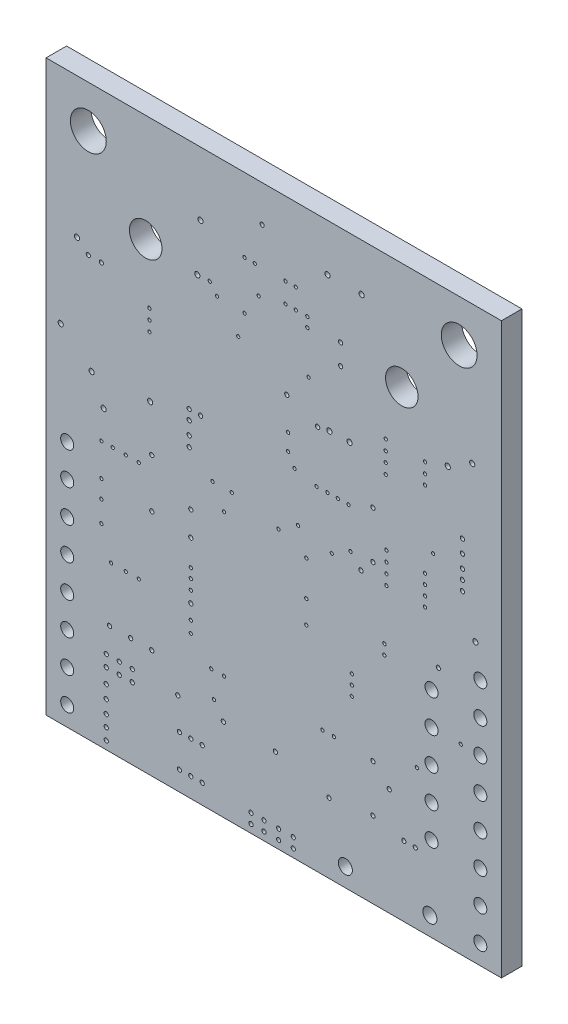
SolidWorks part; units mm, degrees
ref_plane "Front Plane" through (0, 0, 0) normal (0, 0, 1) x (1, 0, 0)
ref_plane "Top Plane" through (0, 0, 0) normal (0, 1, 0) x (1, 0, 0)
ref_plane "Right Plane" through (0, 0, 0) normal (1, 0, 0) x (0, 0, -1)
ref_plane "Dielectric_Layer Layer 1" through (0, 0, 1.6) normal (0, 0, 1) x (1, 0, 0)
sketch "Sketch1" plane through (0, 0, 0) normal (0, 0, 1) x (1, 0, 0)
  line L0 (0, 44.45) -> (0, 0)
  line L1 (0, 0) -> (35.56, 0)
  line L2 (35.56, 0) -> (35.56, 44.45)
  line L3 (35.56, 44.45) -> (0, 44.45)
extrude "Board_Outline" add sketch "Sketch1" along normal blind 1.6 separate body
sketch "Sketch2" plane through (0, 0, 0) normal (0, 0, 1) x (1, 0, 0)
  circle A0 centre (29.591, 23.622) radius 0.127
  circle A1 centre (32.385, 14.224) radius 0.127
  circle A2 centre (20.32, 18.034) radius 0.127
  circle A3 centre (13.111, 7.6) radius 0.127
  circle A4 centre (18.7, 37.15) radius 0.127
  circle A5 centre (19.676, 22.67) radius 0.127
  circle A6 centre (16.3, 38.7) radius 0.127
  circle A7 centre (18.149, 21.651) radius 0.127
  circle A8 centre (18.7, 38.7) radius 0.127
  circle A9 centre (20.322, 20.778) radius 0.127
  circle A10 centre (12.78, 35.731) radius 0.127
  circle A11 centre (19.5, 37.15) radius 0.127
  circle A12 centre (13, 22.3) radius 0.127
  circle A13 centre (13.35, 35) radius 0.127
  circle A14 centre (20.4, 37.15) radius 0.127
  circle A15 centre (18.9, 28.573) radius 0.127
  circle A16 centre (15.5, 38.7) radius 0.127
  circle A17 centre (14.5, 22.3) radius 0.127
  circle A18 centre (19.5, 38.7) radius 0.127
  circle A19 centre (13.9, 20.7) radius 0.127
  circle A20 centre (15.5, 34.925) radius 0.127
  circle A21 centre (12.899, 9.58) radius 0.127
  circle A22 centre (16.6, 36.65) radius 0.127
  circle A23 centre (13.899, 9.58) radius 0.127
  circle A24 centre (20.4, 36.4) radius 0.127
  circle A25 centre (18.9, 27.273) radius 0.127
  circle A26 centre (22.311, 22.097) radius 0.127
  circle A27 centre (20.5, 33.1) radius 0.127
  circle A28 centre (19.399, 26.384) radius 0.127
  circle A29 centre (4.318, 20.701) radius 0.127
  circle A30 centre (4.318, 16.764) radius 0.127
  circle A31 centre (5.08, 12.827) radius 0.127
  circle A32 centre (31.369, 32.512) radius 0.2032
  circle A33 centre (8.255, 21.717) radius 0.1651
  circle A34 centre (5.207, 20.701) radius 0.127
  circle A35 centre (7.239, 12.827) radius 0.127
  circle A36 centre (30.634, 18.515) radius 0.1651
  circle A37 centre (24.592, 22.079) radius 0.1651
  circle A38 centre (33.528, 21.717) radius 0.2032
  circle A39 centre (4.318, 18.161) radius 0.127
  circle A40 centre (4.318, 15.113) radius 0.127
  circle A41 centre (17.018, 0.635) radius 0.1651
  circle A42 centre (16.002, 0.635) radius 0.1651
  circle A43 centre (32.512, 24.638) radius 0.1651
  circle A44 centre (32.512, 25.4) radius 0.1651
  circle A45 centre (28.829, 5.461) radius 0.1651
  circle A46 centre (27.94, 5.461) radius 0.1651
  circle A47 centre (16.002, 1.397) radius 0.1651
  circle A48 centre (17.018, 1.397) radius 0.1651
  circle A49 centre (4.699, 0.635) radius 0.1651
  circle A50 centre (4.699, 1.524) radius 0.1651
  circle A51 centre (4.699, 2.413) radius 0.1651
  circle A52 centre (6.223, 12.827) radius 0.127
  circle A53 centre (7.239, 20.701) radius 0.127
  circle A54 centre (11.303, 17.653) radius 0.1651
  circle A55 centre (6.223, 20.701) radius 0.127
  circle A56 centre (11.176, 26.289) radius 0.1651
  circle A57 centre (12.065, 26.289) radius 0.1651
  circle A58 centre (6.604, 8.509) radius 0.1651
  circle A59 centre (8.255, 8.509) radius 0.1651
  circle A60 centre (10.287, 6.477) radius 0.1651
  circle A61 centre (17.907, 6.477) radius 0.1651
  circle A62 centre (1.143, 27.051) radius 0.2032
  circle A63 centre (4.4958, 22.987) radius 0.2032
  circle A64 centre (25.527, 26.797) radius 0.1651
  circle A65 centre (25.527, 5.969) radius 0.1651
  circle A66 centre (32.512, 26.162) radius 0.1651
  circle A67 centre (12.192, 4.064) radius 0.1651
  circle A68 centre (12.192, 1.524) radius 0.1651
  circle A69 centre (10.414, 1.524) radius 0.1651
  circle A70 centre (10.414, 4.064) radius 0.1651
  circle A71 centre (11.303, 4.064) radius 0.1651
  circle A72 centre (11.303, 1.524) radius 0.1651
  circle A73 centre (16.873, 41.6) radius 0.1651
  circle A74 centre (23, 35.1) radius 0.1651
  circle A75 centre (22.127, 30.273) radius 0.2032
  circle A76 centre (18.8, 31.0635) radius 0.1651
  circle A77 centre (11.303, 13.208) radius 0.1651
  circle A78 centre (26.5746, 23.641) radius 0.127
  circle A79 centre (21.209, 30.099) radius 0.1651
  circle A80 centre (11.176, 25.527) radius 0.1651
  circle A81 centre (24.638, 40.767) radius 0.2032
  circle A82 centre (11.811, 35.687) radius 0.2032
  circle A83 centre (21.59, 9.779) radius 0.127
  circle A84 centre (22.479, 9.779) radius 0.127
  circle A85 centre (11.303, 14.097) radius 0.127
  circle A86 centre (8.071, 29.953) radius 0.127
  circle A87 centre (11.303, 14.883) radius 0.127
  circle A88 centre (8.071, 30.753) radius 0.127
  circle A89 centre (11.303, 15.621) radius 0.127
  circle A90 centre (8.071, 31.553) radius 0.127
  circle A91 centre (23, 36.7) radius 0.1651
  circle A92 centre (3.556, 25.019) radius 0.2032
  circle A93 centre (2.413, 33.528) radius 0.2032
  circle A94 centre (20.32, 16.256) radius 0.127
  circle A95 centre (29.591, 24.384) radius 0.127
  circle A96 centre (19.304, 0.635) radius 0.1651
  circle A97 centre (19.304, 1.397) radius 0.1651
  circle A98 centre (18.161, 1.397) radius 0.1651
  circle A99 centre (18.161, 0.635) radius 0.1651
  circle A100 centre (30.226, 26.035) radius 0.127
  circle A101 centre (21.117, 26.019) radius 0.127
  circle A102 centre (29.591, 22.86) radius 0.127
  circle A103 centre (26.416, 17.272) radius 0.127
  circle A104 centre (29.591, 22.098) radius 0.127
  circle A105 centre (26.416, 18.034) radius 0.127
  circle A106 centre (22.7838, 26.035) radius 0.127
  circle A107 centre (29.591, 31.115) radius 0.127
  circle A108 centre (21.971, 26.035) radius 0.127
  circle A109 centre (29.591, 30.353) radius 0.127
  circle A110 centre (29.591, 31.9278) radius 0.127
  circle A111 centre (23.622, 26.035) radius 0.127
  circle A112 centre (11.303, 11.176) radius 0.127
  circle A113 centre (11.303, 12.065) radius 0.127
  circle A114 centre (23.78, 22.956) radius 0.127
  circle A115 centre (23.876, 13.208) radius 0.127
  circle A116 centre (23.876, 13.97) radius 0.127
  circle A117 centre (28.956, 10.922) radius 0.127
  circle A118 centre (23.876, 14.732) radius 0.127
  circle A119 centre (22.098, 5.461) radius 0.1651
  circle A120 centre (26.797, 8.382) radius 0.1651
  circle A121 centre (11.303, 19.558) radius 0.1651
  circle A122 centre (25.527, 23.114) radius 0.1651
  circle A123 centre (32.512, 27.178) radius 0.1651
  circle A124 centre (32.512, 28.194) radius 0.1651
  circle A125 centre (5.715, 6.477) radius 0.1651
  circle A126 centre (4.699, 6.477) radius 0.1651
  circle A127 centre (6.731, 6.477) radius 0.1651
  circle A128 centre (11.176, 24.511) radius 0.1651
  circle A129 centre (8.255, 17.907) radius 0.1651
  circle A130 centre (4.318, 32.766) radius 0.1651
  circle A131 centre (11.176, 23.711) radius 0.1651
  circle A132 centre (6.731, 5.588) radius 0.1651
  circle A133 centre (5.715, 5.588) radius 0.1651
  circle A134 centre (4.953, 8.509) radius 0.1651
  circle A135 centre (13.843, 6.477) radius 0.1651
  circle A136 centre (25.527, 9.652) radius 0.1651
  circle A137 centre (4.699, 3.429) radius 0.1651
  circle A138 centre (4.699, 4.445) radius 0.1651
  circle A139 centre (4.699, 5.588) radius 0.1651
  circle A140 centre (3.302, 32.766) radius 0.1651
  circle A141 centre (15, 33.1) radius 0.127
  circle A142 centre (26.5746, 22.041) radius 0.127
  circle A143 centre (26.5746, 22.841) radius 0.127
  circle A144 centre (26.5746, 24.441) radius 0.127
  circle A145 centre (26.524, 31.934) radius 0.127
  circle A146 centre (26.524, 31.134) radius 0.127
  circle A147 centre (26.524, 30.334) radius 0.127
  circle A148 centre (26.524, 29.534) radius 0.127
  circle A149 centre (33.274, 33.655) radius 0.2032
  circle A150 centre (23.7, 30.304) radius 0.2032
  circle A151 centre (21.971, 40.767) radius 0.2032
  circle A152 centre (8.128, 25.273) radius 0.2032
  circle A153 centre (12.065, 39.497) radius 0.2032
extrude "NPTH" cut sketch "Sketch2" along normal through all
sketch "Sketch3" plane through (0, 0, 0) normal (0, 0, 1) x (1, 0, 0)
  circle A0 centre (3.3, 41.15) radius 1.4
  circle A1 centre (32.26, 41.15) radius 1.4
  circle A2 centre (33.91, 19.3) radius 0.51
  circle A3 centre (33.91, 16.76) radius 0.51
  circle A4 centre (33.91, 14.22) radius 0.51
  circle A5 centre (33.91, 11.68) radius 0.51
  circle A6 centre (33.91, 9.14) radius 0.51
  circle A7 centre (33.91, 6.6) radius 0.51
  circle A8 centre (33.91, 4.06) radius 0.51
  circle A9 centre (33.91, 1.52) radius 0.51
  circle A10 centre (1.65, 19.3) radius 0.51
  circle A11 centre (1.65, 16.76) radius 0.51
  circle A12 centre (1.65, 14.22) radius 0.51
  circle A13 centre (1.65, 11.68) radius 0.51
  circle A14 centre (1.65, 9.14) radius 0.51
  circle A15 centre (1.65, 6.6) radius 0.51
  circle A16 centre (1.65, 4.06) radius 0.51
  circle A17 centre (1.65, 1.52) radius 0.51
  circle A18 centre (30.1, 16.76) radius 0.51
  circle A19 centre (30.1, 14.22) radius 0.51
  circle A20 centre (30.1, 11.68) radius 0.51
  circle A21 centre (30.1, 9.14) radius 0.51
  circle A22 centre (30.1, 6.6) radius 0.51
  circle A23 centre (7.78, 36.07) radius 1.27
  circle A24 centre (27.78, 36.07) radius 1.27
  circle A25 centre (23.37, 1.45) radius 0.55
  circle A26 centre (29.97, 1.45) radius 0.55
extrude "PTH" cut sketch "Sketch3" along normal through all
sketch "Sketch4" plane through (0, 0, 1.6) normal (0, 0, 1) x (1, 0, 0)
  circle A0 centre (32.26, 41.15) radius 1.4 construction
  circle A1 centre (3.3, 41.15) radius 1.4 construction
  circle A2 centre (32.26, 41.15) radius 1.4
  circle A3 centre (3.3, 41.15) radius 1.4
  dimension "D1" = 28.96
sketch "Sketch7" plane through (0, 0, 1.6) normal (0, 0, 1) x (1, 0, 0)
  line L1 (0, 22.225) -> (35.56, 22.225)
  line L2 (0, 44.45) -> (35.56, 44.45)
  line L3 (0, 44.45) -> (0, 0)
  line L4 (0, 0) -> (35.56, 0)
  line L5 (35.56, 44.45) -> (35.56, 0)
  circle A0 centre (1.65, 19.3) radius 0.51 construction
  circle A1 centre (1.65, 1.52) radius 0.51 construction
  circle A2 centre (3.3, 41.15) radius 1.4 construction
  dimension "D1" = 17.78
  dimension "D2" = 21.85
